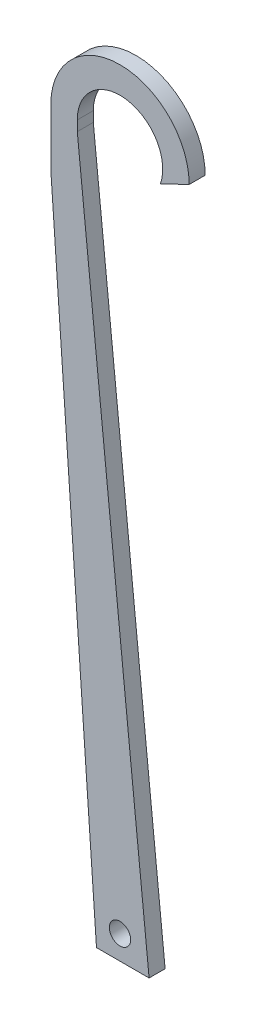
SolidWorks part; units mm, degrees
ref_plane "Front Plane" through (0, 0, 0) normal (0, 0, 1) x (1, 0, 0)
ref_plane "Top Plane" through (0, 0, 0) normal (0, 1, 0) x (1, 0, 0)
ref_plane "Right Plane" through (0, 0, 0) normal (1, 0, 0) x (0, 0, -1)
sketch "Sketch1" plane through (0, 0, 0) normal (0, 0, 1) x (1, 0, 0)
  line L0 (-25.4, 0) -> (-25.4, -6.0529)
  line L1 (24.0316, -8.2244) -> (41.1442, 0)
  line L2 (-41.1442, 0) -> (-41.1442, -33.7315)
  line L3 (0, 0) -> (0, -406.4) construction
  line L4 (-41.1442, -33.7315) -> (-13.977, -420.5808)
  line L5 (-13.977, -420.5808) -> (17.3106, -420.5808)
  line L6 (17.3106, -420.5808) -> (-25.4, -6.0529)
  circle A0 centre (0, 0) radius 25.4 construction
  arc A1 (-25.4, 0) -> (25.4, 0) centre (0, 0) cw
  arc A2 (25.4, 0) -> (24.0316, -8.2244) centre (0, 0) cw
  arc A3 (41.1442, 0) -> (-41.1442, 0) centre (0, 0) ccw
  circle A4 centre (0, -406.4) radius 6.35
  point P14 (-32.8069, 0)
  point P17 (44.4953, 0)
  point P18 (-43.7182, -32.3038)
  point P19 (-55.9638, 0)
  point P20 (-52.5247, -26.1585)
  point P21 (47.5219, 0)
  point P22 (-50.4036, -77.2239)
  point P23 (-37.9554, -79.139)
  point P24 (-25.4, -34.2841)
  point P25 (-24.5721, -6.4321)
  point P26 (-25.4, -14.3026)
  point P27 (-41.1442, 0)
  point P28 (-25.4, -39.3585)
  dimension "D1" = 50.8
  dimension "D3" = 12.7
  dimension "D2" = 406.4
extrude "Boss-Extrude1" add sketch "Sketch1" along normal blind 9.525
